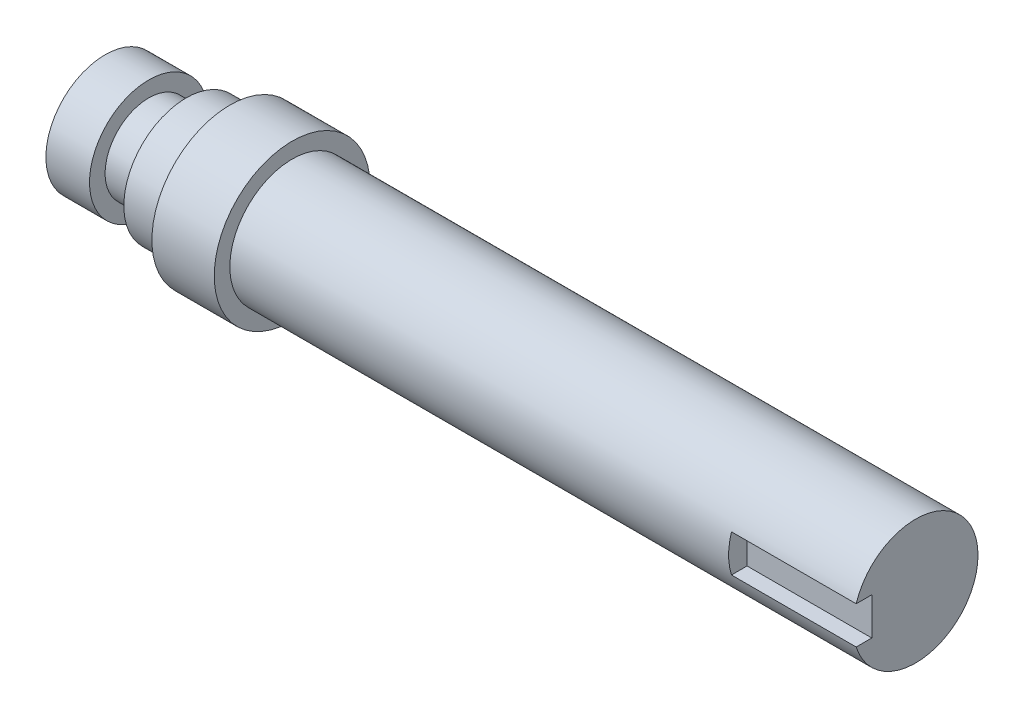
SolidWorks part; units mm, degrees
ref_plane "Front Plane" through (0, 0, 0) normal (0, 0, 1) x (1, 0, 0)
ref_plane "Top Plane" through (0, 0, 0) normal (0, 1, 0) x (1, 0, 0)
ref_plane "Right Plane" through (0, 0, 0) normal (1, 0, 0) x (0, 0, -1)
sketch "Sketch1" plane through (0, 0, 0) normal (0, 0, 1) x (1, 0, 0)
  line L0 (0, 0) -> (0, 9.5)
  line L1 (0, 9.5) -> (7, 9.5)
  line L2 (7, 9.5) -> (7, 7)
  line L3 (7, 7) -> (13, 7)
  line L4 (13, 7) -> (13, 10)
  line L5 (13, 10) -> (20, 10)
  line L6 (20, 10) -> (20, 12.5)
  line L7 (20, 12.5) -> (30, 12.5)
  line L8 (30, 12.5) -> (30, 10)
  line L9 (30, 10) -> (130, 10)
  line L10 (130, 10) -> (130, 0)
  line L11 (130, 0) -> (0, 0)
  dimension "D1" = 130
  dimension "D2" = 100
  dimension "D3" = 7
  dimension "D4" = 6
  dimension "D5" = 10
  dimension "D6" = 10
  dimension "D7" = 9.5
  dimension "D8" = 7
  dimension "D9" = 10
  dimension "D10" = 12.5
revolve "Revolve1" add sketch "Sketch1" angle 360 about L11
sketch "Sketch2" plane through (130, 0, 0) normal (1, 0, 0) x (0, 0, -1)
  line L0 (0, 0) -> (-22.3874, 0) construction
  line L1 (-9.5394, 3) -> (-7.0394, 3)
  line L3 (-9.5394, -3) -> (-7.0394, -3)
  line L4 (-7.0394, 3) -> (-7.0394, -3)
  circle A2 centre (0, 0) radius 10 construction
  arc A3 (-9.5394, 3) -> (-9.5394, -3) centre (0, 0) ccw
  dimension "D1" = 6
  dimension "D2" = 2.5
extrude "Cut-Extrude1" cut sketch "Sketch2" against normal blind 20
